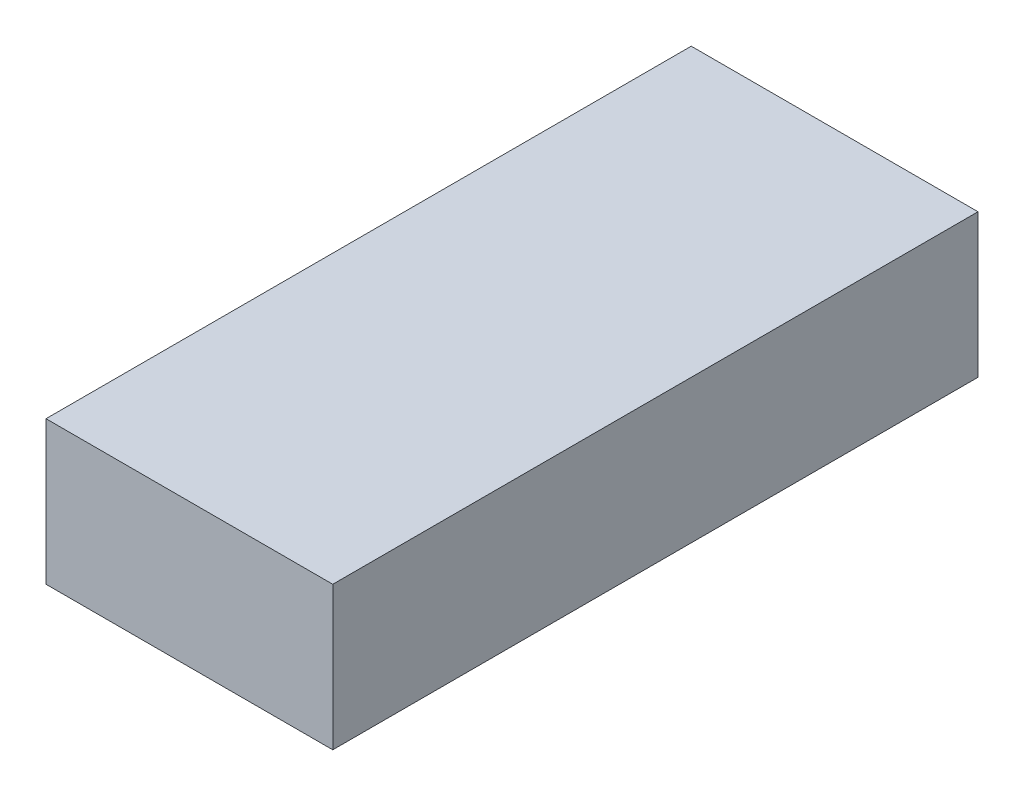
SolidWorks part; units mm, degrees
ref_plane "前视基准面" through (0, 0, 0) normal (0, 0, 1) x (1, 0, 0)
ref_plane "上视基准面" through (0, 0, 0) normal (0, 1, 0) x (1, 0, 0)
ref_plane "右视基准面" through (0, 0, 0) normal (1, 0, 0) x (0, 0, -1)
other "Configuration Table"
sketch "草图1" plane through (0, 0, 0) normal (0, 0, 1) x (1, 0, 0)
  line L1 (-400, -200) -> (400, -200)
  line L2 (-400, -200) -> (-400, 200)
  line L3 (-400, 200) -> (400, 200)
  line L4 (400, -200) -> (400, 200)
  line L5 (-400, -200) -> (400, 200) construction
  line L6 (-400, 200) -> (400, -200) construction
extrude "凸台-拉伸1" add sketch "草图1" along normal blind 1800
sketch "草图2" plane through (0, 0, 0) normal (0, 0, 1) x (1, 0, 0)
  line L1 (-380, -180) -> (380, -180)
  line L2 (-380, -180) -> (-380, 180)
  line L3 (-380, 180) -> (380, 180)
  line L4 (380, -180) -> (380, 180)
  line L5 (-380, -180) -> (380, 180) construction
  line L6 (-380, 180) -> (380, -180) construction
extrude "切除-拉伸2" cut sketch "草图2" along normal blind 50
sketch "草图3" plane through (0, 0, 0) normal (0, 0, 1) x (1, 0, 0)
  line L1 (-380, -10) -> (0, -10)
  line L2 (-380, -10) -> (-380, 10)
  line L3 (-380, 10) -> (0, 10)
  line L4 (0, -10) -> (0, 10)
  line L5 (-380, -10) -> (0, 10) construction
  line L6 (-380, 10) -> (0, -10) construction
extrude "凸台-拉伸2" add sketch "草图3" along normal blind 1700
sketch "草图4" plane through (0, 0, 0) normal (0, 0, 1) x (1, 0, 0)
  line L1 (0, -10) -> (380, -10)
  line L2 (0, -10) -> (0, 10)
  line L3 (0, 10) -> (380, 10)
  line L4 (380, -10) -> (380, 10)
  line L5 (0, -10) -> (380, 10) construction
  line L6 (0, 10) -> (380, -10) construction
extrude "凸台-拉伸3" add sketch "草图4" along normal blind 1700
sketch "草图5" plane through (0, 0, 0) normal (0, 0, 1) x (1, 0, 0)
  line L1 (-380, -10) -> (380, -10)
  line L2 (-380, -10) -> (-380, 10)
  line L3 (-380, 10) -> (380, 10)
  line L4 (380, -10) -> (380, 10)
  line L5 (-380, -10) -> (380, 10) construction
  line L6 (-380, 10) -> (380, -10) construction
extrude "凸台-拉伸4" add sketch "草图5" along normal blind 300
sketch "草图6" plane through (0, 0, 0) normal (0, 0, 1) x (1, 0, 0)
  circle A0 centre (-150, 0) radius 20
extrude "凸台-拉伸5" add sketch "草图6" along normal blind 80
sketch "草图7" plane through (0, 0, 0) normal (0, 0, 1) x (1, 0, 0)
  circle A0 centre (150, 0) radius 20
extrude "凸台-拉伸6" add sketch "草图7" along normal blind 80
